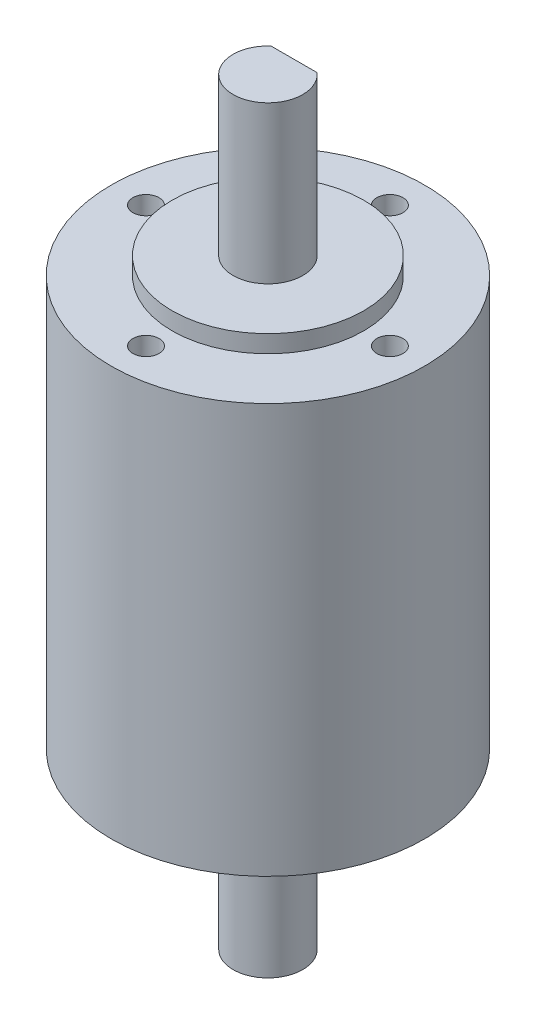
SolidWorks part; units mm, degrees
ref_plane "前视基准面" through (0, 0, 0) normal (0, 0, 1) x (1, 0, 0)
ref_plane "上视基准面" through (0, 0, 0) normal (0, 1, 0) x (1, 0, 0)
ref_plane "右视基准面" through (0, 0, 0) normal (1, 0, 0) x (0, 0, -1)
other "Configuration Table"
sketch "草图1" plane through (0, 0, 0) normal (0, 1, 0) x (1, 0, 0)
  circle A0 centre (0, 0) radius 18
  dimension "D1" = 36
extrude "凸台-拉伸1" add sketch "草图1" along normal blind 47
sketch "草图2" plane through (0, 47, 0) normal (0, 1, 0) x (1, 0, 0)
  circle A0 centre (0, 0) radius 11
  dimension "D1" = 22
extrude "凸台-拉伸2" add sketch "草图2" along normal blind 2
sketch "草图3" plane through (0, 0, 0) normal (0, -1, 0) x (1, 0, 0)
  circle A0 centre (0, 0) radius 11
  dimension "D1" = 22
extrude "凸台-拉伸3" add sketch "草图3" along normal blind 2
sketch "草图4" plane through (0, -2, 0) normal (0, -1, 0) x (1, 0, 0)
  circle A0 centre (0, 0) radius 4
  dimension "D1" = 8
extrude "凸台-拉伸4" add sketch "草图4" along normal blind 18
sketch "草图5" plane through (0, 49, 0) normal (0, 1, 0) x (1, 0, 0)
  circle A0 centre (0, 0) radius 4
  dimension "D1" = 8
extrude "凸台-拉伸5" add sketch "草图5" along normal blind 18
sketch "草图6" plane through (0, 67, 0) normal (0, 1, 0) x (1, 0, 0)
  line L1 (-4.794, 3) -> (4.4584, 3)
  line L2 (-4.794, 3) -> (-4.794, 7.6022)
  line L3 (-4.794, 7.6022) -> (4.4584, 7.6022)
  line L4 (4.4584, 3) -> (4.4584, 7.6022)
  dimension "D1" = 3
extrude "切除-拉伸1" cut sketch "草图6" against normal blind 15
sketch "草图7" plane through (0, -20, 0) normal (0, -1, 0) x (1, 0, 0)
  line L4 (4.4584, -3) -> (-4.794, -3)
  line L5 (4.4584, -7.6022) -> (4.4584, -3)
  line L6 (-4.794, -7.6022) -> (4.4584, -7.6022)
  line L7 (-4.794, -3) -> (-4.794, -7.6022)
  line L8 (4.4584, -3) -> (-4.794, -3)
  line L9 (4.4584, -7.6022) -> (4.4584, -3)
  line L10 (-4.794, -7.6022) -> (4.4584, -7.6022)
  line L11 (-4.794, -3) -> (-4.794, -7.6022)
  dimension "D1" = 0
extrude "切除-拉伸2" cut sketch "草图7" against normal blind 15
sketch "草图8" plane through (0, 0, 0) normal (0, -1, 0) x (1, 0, 0)
  line L0 (0, 0) -> (0, 14) construction
  circle A0 centre (0, 14) radius 1.5
  circle A1 centre (14, 0) radius 1.5
  circle A2 centre (0, -14) radius 1.5
  circle A3 centre (-14, 0) radius 1.5
  point P13 (0, 0)
  dimension "D1" = 3
  dimension "D2" = 14
  dimension "D3" = 4
extrude "切除-拉伸3" cut sketch "草图8" against normal blind 6
sketch "草图9" plane through (0, 47, 0) normal (0, 1, 0) x (1, 0, 0)
  circle A1 centre (-14, 0) radius 1.5
  circle A2 centre (-14, 0) radius 1.5
  circle A3 centre (0, 14) radius 1.5
  circle A4 centre (0, 14) radius 1.5
  circle A5 centre (14, 0) radius 1.5
  circle A6 centre (14, 0) radius 1.5
  circle A7 centre (0, -14) radius 1.5
  circle A8 centre (0, -14) radius 1.5
  dimension "D1" = 0
  dimension "D2" = 0
  dimension "D3" = 0
  dimension "D4" = 0
extrude "切除-拉伸4" cut sketch "草图9" against normal blind 6
